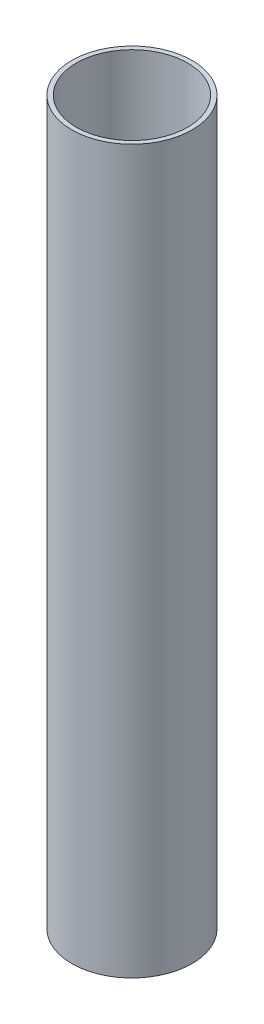
SolidWorks part; units mm, degrees
material "6061-T6 (SS)"
ref_plane "Front Plane" through (0, 0, 0) normal (0, 0, 1) x (1, 0, 0)
ref_plane "Top Plane" through (0, 0, 0) normal (0, 1, 0) x (1, 0, 0)
ref_plane "Right Plane" through (0, 0, 0) normal (1, 0, 0) x (0, 0, -1)
sketch "Sketch1" plane through (0, 0, 0) normal (0, 1, 0) x (1, 0, 0)
  circle A0 centre (0, 0) radius 9.525
  circle A1 centre (0, 0) radius 8.8138
  dimension "D1" = 0.7112
  dimension "D2" = 19.05
extrude "Boss-Extrude1" add sketch "Sketch1" along normal blind 114.3
